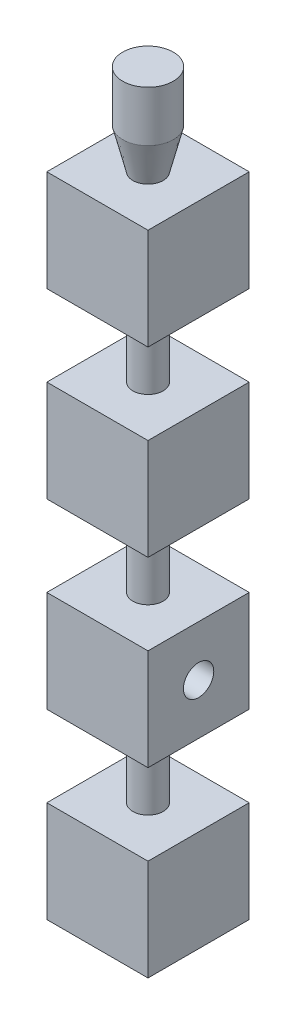
SolidWorks part; units mm, degrees
ref_plane "Front Plane" through (0, 0, 0) normal (0, 0, 1) x (1, 0, 0)
ref_plane "Top Plane" through (0, 0, 0) normal (0, 1, 0) x (1, 0, 0)
ref_plane "Right Plane" through (0, 0, 0) normal (1, 0, 0) x (0, 0, -1)
sketch "Sketch1" plane through (0, 0, 0) normal (0, 1, 0) x (1, 0, 0)
  line L1 (0, 0) -> (12.7, 0)
  line L2 (0, 0) -> (0, -12.7)
  line L3 (0, -12.7) -> (12.7, -12.7)
  line L4 (12.7, 0) -> (12.7, -12.7)
  dimension "D1" = 12.7
extrude "Boss-Extrude1" add sketch "Sketch1" along normal blind 12.7
sketch "Sketch2" plane through (0, 12.7, 0) normal (0, 1, 0) x (1, 0, 0)
  line L0 (0, 0) -> (12.7, -12.7) construction
  line L1 (0, -12.7) -> (12.7, 0) construction
  circle A0 centre (6.35, -6.35) radius 1.905
  point P11 (6.35, -6.35)
  dimension "D1" = 3.81
extrude "Boss-Extrude2" add sketch "Sketch2" along normal blind 5.08
ref_plane "Plane1" through (0, 17.78, 0) normal (0, 1, 0) x (1, 0, 0)
mirror "Mirror4" about plane through (0, 17.78, 0) normal (0, 1, 0) of "Boss-Extrude1", "Boss-Extrude2"
sketch "Sketch4" plane through (0, 35.56, 0) normal (0, 1, 0) x (1, 0, 0)
  line L1 (0, 0) -> (12.7, -12.7) construction
  line L2 (0, -12.7) -> (12.7, 0) construction
  circle A0 centre (6.35, -6.35) radius 1.905
  point P4 (6.35, -6.35)
  dimension "D1" = 3.81
extrude "Boss-Extrude3" add sketch "Sketch4" along normal blind 5.08
ref_plane "Plane2" through (0, 40.64, 0) normal (0, 1, 0) x (1, 0, 0)
mirror "Mirror5" about plane through (0, 40.64, 0) normal (0, 1, 0) of "Boss-Extrude3", "Mirror4"
sketch "Sketch5" plane through (0, 45.72, 0) normal (0, 1, 0) x (1, 0, 0)
  line L1 (0, -12.7) -> (12.7, -12.7)
  line L2 (0, -12.7) -> (0, 0)
  line L3 (0, 0) -> (12.7, 0)
  line L4 (12.7, -12.7) -> (12.7, 0)
extrude "Boss-Extrude4" add sketch "Sketch5" along normal blind 12.7
sketch "Sketch6" plane through (0, 58.42, 0) normal (0, 1, 0) x (1, 0, 0)
  line L0 (0, 0) -> (0, -12.7) construction
  line L1 (12.7, 0) -> (0, 0) construction
  circle A0 centre (6.35, -6.35) radius 1.905
  point P5 (0, -6.35)
  point P8 (6.35, 0)
  dimension "D1" = 3.81
extrude "Boss-Extrude5" add sketch "Sketch6" along normal blind 5.08
ref_plane "Plane3" through (0, 63.5, 0) normal (0, 1, 0) x (1, 0, 0)
mirror "Mirror6" about plane through (0, 63.5, 0) normal (0, 1, 0) of "Boss-Extrude5", "Boss-Extrude4"
sketch "Sketch7" plane through (0, 81.28, 0) normal (0, 1, 0) x (1, 0, 0)
  line L0 (0, 0) -> (0, -12.7) construction
  line L1 (12.7, 0) -> (0, 0) construction
  circle A0 centre (6.35, -6.35) radius 1.905
  point P4 (0, -6.35)
  point P7 (6.35, 0)
  dimension "D1" = 3.81
extrude "Boss-Extrude7" add sketch "Sketch7" along normal blind 5.08 draft 14
sketch "Sketch9" plane through (0, 86.36, 0) normal (0, 1, 0) x (1, 0, 0)
  circle A0 centre (6.35, -6.35) radius 3.1716
  circle A1 centre (6.35, -6.35) radius 3.1716 construction
extrude "Boss-Extrude8" add sketch "Sketch9" along normal blind 6.35
sketch "Sketch10" plane through (12.7, 0, 0) normal (1, 0, 0) x (0, 0, -1)
  line L1 (-12.7, 12.7) -> (0, 12.7) construction
  line L2 (-12.7, 22.86) -> (-12.7, 35.56) construction
  circle A0 centre (-6.35, 29.21) radius 1.905
  point P7 (-6.35, 12.7)
  point P10 (-12.7, 29.21)
  dimension "D1" = 3.81
extrude "Cut-Extrude1" cut sketch "Sketch10" against normal blind 6.35
equation "\"Connector Height\"= .2"
equation "\"Connector Diameter\"= .15"
equation "\"Block Height\"= 0.5"
equation "\"D1@Sketch2\"=\"Connector Diameter\""
equation "\"D1@Boss-Extrude2\"=\"Connector Height\""
equation "\"D1@Sketch1\"=\"Block Height\""
equation "\"D1@Boss-Extrude1\"=\"Block Height\""
equation "\"D1@Sketch4\"=\"Connector Diameter\""
equation "\"D1@Boss-Extrude3\"=\"Connector Height\""
equation "\"D1@Boss-Extrude4\"=\"Block Height\""
equation "\"D1@Sketch6\"=\"Connector Diameter\""
equation "\"D1@Boss-Extrude5\"=\"Connector Height\""
equation "\"D1@Sketch7\"=\"Connector Diameter\""
equation "\"D1@Sketch10\"=\"Connector Diameter\""
